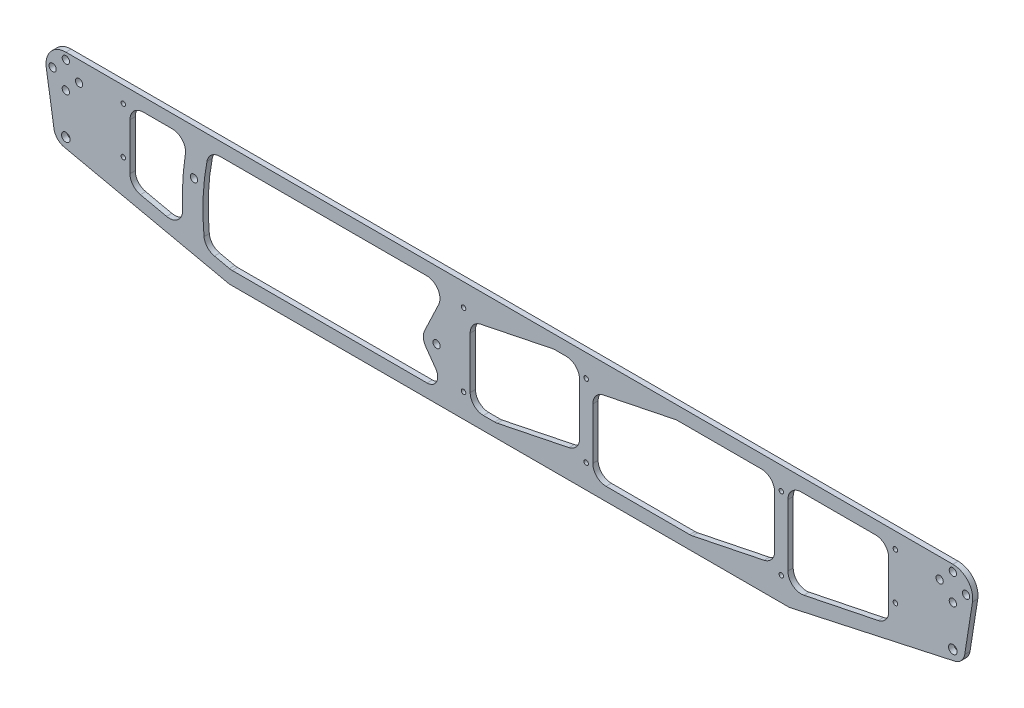
SolidWorks part; units mm, degrees
material "Сплав 2024"
ref_plane "Спереди" through (0, 0, 0) normal (0, 0, 1) x (1, 0, 0)
ref_plane "Сверху" through (0, 0, 0) normal (0, 1, 0) x (1, 0, 0)
ref_plane "Справа" through (0, 0, 0) normal (1, 0, 0) x (0, 0, -1)
sketch "Эскиз1" plane through (0, 0, 0) normal (0, 0, 1) x (1, 0, 0)
  line L0 (-349.8183, 27.6724) -> (-342.9109, -16.3036)
  line L1 (-350, 45) -> (350, 45) construction
  line L2 (-350, 45) -> (-350, -45) construction
  line L3 (-350, -45) -> (350, -45) construction
  line L4 (350, 45) -> (350, -45) construction
  line L5 (-350, 45) -> (350, -45) construction
  line L6 (-350, -45) -> (350, 45) construction
  line L7 (-342.9109, -16.3036) -> (-211.4811, -45)
  line L9 (0, 62.4154) -> (0, -74.3401) construction
  line L10 (-211.4811, -45) -> (211.4811, -45)
  line L12 (-335, 45) -> (335, 45)
  line L15 (342.9109, -16.3036) -> (211.4811, -45)
  line L16 (349.8183, 27.6724) -> (342.9109, -16.3036)
  arc A0 (-335, 45) -> (-349.8183, 27.6724) centre (-335, 30) ccw
  arc A1 (335, 45) -> (349.8183, 27.6724) centre (335, 30) cw
  circle A2 centre (-335, -10.6353) radius 3.25
  circle A3 centre (335, -10.6353) radius 3.25
  point P0 (0, 0)
  point P20 (0, 45)
  point P21 (0, -45)
  dimension "D3" = 30
  dimension "D4" = 6.5
  dimension "D1" = 700
  dimension "D2" = 90
extrude "Бобышка-Вытянуть1" add sketch "Эскиз1" along normal blind 4
sketch "Эскиз2" plane through (0, 0, 4) normal (0, 0, 1) x (1, 0, 0)
  line L0 (0, 49.4785) -> (0, -75.5602) construction
  line L1 (-350, 30) -> (-320, 30) construction
  line L2 (-335, 45) -> (-335, 15) construction
  line L3 (335, 45) -> (335, 15) construction
  line L4 (350, 30) -> (320, 30) construction
  circle A0 centre (-335, 30) radius 15 construction
  arc A1 (-335, 45) -> (-349.8183, 27.6724) centre (-335, 30) ccw construction
  circle A2 centre (-335, 30) radius 10 construction
  circle A4 centre (335, 30) radius 10 construction
  circle A5 centre (335, 30) radius 15 construction
  dimension "D2" = 20
hole_wizard "Отверстие с зазором M51" positions "Эскиз4" profile "Эскиз3" hole size "M5" standard "Ansi Metric" end condition through all
sketch "Эскиз4" plane through (0, 0, 4) normal (0, 0, 1) x (1, 0, 0)
  line L0 (-335, 45) -> (-335, 15) construction
  line L1 (-350, 30) -> (-320, 30) construction
  line L2 (350, 30) -> (320, 30) construction
  line L3 (335, 45) -> (335, 15) construction
  circle A0 centre (-335, 30) radius 10 construction
  circle A1 centre (335, 30) radius 10 construction
  point P0 (-335, 40)
  point P6 (-345, 30)
  point P10 (-335, 20)
  point P12 (-325, 30)
  point P34 (325, 30)
  point P40 (335, 40)
  point P44 (345, 30)
  point P46 (335, 20)
sketch "Эскиз3" plane through (-335, 40, 4) normal (1, 0, 0) x (0, -1, 0)
  line L0 (0, 0) -> (0, 4)
  line L1 (0, 4) -> (2.75, 4)
  line L2 (2.75, 4) -> (2.75, 0)
  line L5 (2.75, 0) -> (0, 0)
  line L11 (0, -6.35) -> (0, 107.95) construction
  dimension "Диаметр сквозного отверстия" = 5.5
  dimension "Глубина сквозного отверстия" = 4
sketch "Эскиз7" plane through (0, 0, 0) normal (0, 0, -1) x (-1, 0, 0)
  line L0 (211.4811, -45) -> (-211.4811, -45) construction
  arc A0 (349.8183, 27.6724) -> (335, 45) centre (335, 30) ccw construction
  point P0 (55, -6)
  point P4 (238.23, 10.84)
  dimension "D1" = 183.23
  dimension "D2" = 16.84
  dimension "D3" = 280
  dimension "D4" = 39
hole_wizard "Отверстие с зазором M52" positions "Эскиз9" profile "Эскиз8" hole size "M5" standard "Ansi Metric" end condition through all
sketch "Эскиз9" plane through (0, 0, 0) normal (0, 0, -1) x (-1, 0, 0)
  point P0 (55, -6)
  point P3 (238.23, 10.84)
sketch "Эскиз8" plane through (-55, -6, 0) normal (1, 0, 0) x (0, 1, 0)
  line L0 (0, 0) -> (0, 4)
  line L1 (0, 4) -> (2.75, 4)
  line L2 (2.75, 4) -> (2.75, 0)
  line L5 (2.75, 0) -> (0, 0)
  line L11 (0, -6.35) -> (0, 107.95) construction
  dimension "Диаметр сквозного отверстия" = 5.5
  dimension "Глубина сквозного отверстия" = 4
sketch "Эскиз10" plane through (0, 0, 4) normal (0, 0, 1) x (1, 0, 0)
  line L0 (-286.5713, 35) -> (-242.5713, 35)
  line L1 (335, 45) -> (-335, 45) construction
  line L2 (-286.5713, 35) -> (-286.5713, -18.3692)
  line L3 (-286.5713, -18.3692) -> (-245.8185, -27.2672)
  line L4 (0, 45) -> (0, -45) construction
  line L5 (-342.9109, -16.3036) -> (-211.4811, -45) construction
  line L6 (-226.6719, 35) -> (-46.5878, 35)
  line L7 (-210.4021, -35) -> (-46.5878, -35)
  line L8 (-211.4811, -45) -> (211.4811, -45) construction
  line L9 (-210.4021, -35) -> (-229.7525, -30.775)
  line L10 (-46.5878, 35) -> (-64.032, -1.7078)
  line L11 (-46.5878, -35) -> (-63.1395, -11.8093)
  line L12 (286.5713, 35) -> (286.5713, -18.3692)
  line L13 (286.5713, -18.3692) -> (210.4021, -34)
  line L14 (286.5713, 35) -> (210.4021, 35)
  line L15 (210.4021, 35) -> (210.4021, -34)
  line L16 (210.4021, -42) -> (210.4021, 43) construction
  line L17 (200.4021, 35) -> (126.1451, 35)
  line L18 (200.4021, -42) -> (200.4021, 43) construction
  line L19 (-29.5979, -42) -> (-29.5979, 43) construction
  line L20 (-29.5979, 22.0494) -> (-29.5979, -35)
  line L21 (-29.5979, -35) -> (-10.0721, -35)
  line L22 (200.4021, -22.0494) -> (200.4021, 35)
  line L23 (53.0365, 35) -> (53.0365, -22.0494)
  line L24 (63.0365, 22.0494) -> (63.0365, -35)
  line L25 (33.5107, 35) -> (-29.5979, 22.0494)
  line L26 (200.4021, -22.0494) -> (137.2934, -35)
  line L28 (63.0365, -35) -> (137.2934, -35)
  line L29 (126.1451, 35) -> (63.0365, 22.0494)
  line L30 (53.0365, -22.0494) -> (-10.0721, -35)
  line L34 (53.0365, 35) -> (33.5107, 35)
  arc A0 (-64.032, -1.7078) -> (-63.1395, -11.8093) centre (-55, -6) ccw
  arc A2 (-242.5713, 35) -> (-245.8185, -27.2672) centre (-55, -6) ccw
  arc A3 (-226.6719, 35) -> (-229.7525, -30.775) centre (-55, -6) ccw
  dimension "D4" = 384
  dimension "D5" = 353
  dimension "D2" = 20
  dimension "D1" = 10
  dimension "D3" = 10
  dimension "D6" = 10
  dimension "D7" = 10
  dimension "D8" = 10
  dimension "D9" = 44
  dimension "D10" = 10
  dimension "D11" = 57.0494
extrude "Вырез-Вытянуть3" cut sketch "Эскиз10" against normal through all
fillet "Скругление2" radius 10 16 edges at (-46.5878, 35, 2) (-210.4021, -35, 2) (-229.7525, -30.775, 2) (-226.6719, 35, 2) (-242.5713, 35, 2) (-245.8185, -27.2672, 2) (-286.5713, -18.3692, 2) (-286.5713, 35, 2) (-342.9109, -16.3036, 2) (-211.4811, -45, 2) (211.4811, -45, 2) (342.9109, -16.3036, 2) (286.5713, 35, 2) (286.5713, -18.3692, 2) (210.4021, 35, 2) (210.4021, -34, 2)
fillet "Скругление3" radius 10 12 edges at (-29.5979, -35, 2) (200.4021, 35, 2) (53.0365, 35, 2) (200.4021, -22.0494, 2) (137.2934, -35, 2) (33.5107, 35, 2) (-29.5979, 22.0494, 2) (63.0365, -35, 2) (126.1451, 35, 2) (63.0365, 22.0494, 2) (53.0365, -22.0494, 2) (-10.0721, -35, 2)
sketch "Эскиз11" plane through (0, 0, 4) normal (0, 0, 1) x (1, 0, 0)
  line L0 (205.4021, 45) -> (205.4021, -45) construction
  line L1 (335, 45) -> (-335, 45) construction
  line L2 (-210.4021, -45) -> (210.4021, -45) construction
  line L3 (200.4021, -13.8931) -> (200.4021, 25) construction
  line L4 (199.8709, -27) -> (211.9144, -27) construction
  line L5 (202.3145, 28) -> (208.249, 28) construction
  line L6 (-34.5979, 45) -> (-34.5979, -45) construction
  line L7 (-29.5979, 13.8931) -> (-29.5979, -25) construction
  line L8 (-39.6608, -27) -> (-30.9685, -27) construction
  line L9 (-37.6326, 28) -> (-30.9685, 28) construction
  line L10 (291.5713, 36.1496) -> (291.5713, -11.5594) construction
  line L11 (286.5713, -10.2129) -> (286.5713, 25) construction
  line L12 (294.823, -2) -> (288.4097, -2) construction
  line L13 (294.823, 33) -> (288.4097, 33) construction
  line L14 (0, 45) -> (0, 71.0849) construction
  line L15 (-294.823, 33) -> (-288.4097, 33) construction
  line L16 (-294.823, -2) -> (-288.4097, -2) construction
  line L17 (-291.5713, 36.1496) -> (-291.5713, -11.5594) construction
  line L18 (58.0365, 45) -> (58.0365, -45) construction
  line L19 (53.0365, -13.8931) -> (53.0365, 25) construction
  line L20 (53.8048, -27) -> (63.1419, -27) construction
  line L21 (64.656, 28) -> (53.8048, 28) construction
  dimension "D1" = 5
  dimension "D2" = 18
  dimension "D3" = 55
  dimension "D4" = 5
  dimension "D5" = 18
  dimension "D6" = 55
  dimension "D7" = 5
  dimension "D8" = 35
  dimension "D9" = 5
  dimension "D10" = 18
  dimension "D11" = 55
hole_wizard "Отверстие с зазором M31" positions "Эскиз13" profile "Эскиз12" hole size "M3" standard "Ansi Metric" end condition through all
sketch "Эскиз13" plane through (0, 0, 4) normal (0, 0, 1) x (1, 0, 0)
  line L0 (-34.5979, 45) -> (-34.5979, -45) construction
  line L1 (-37.6326, 28) -> (-30.9685, 28) construction
  line L2 (-39.6608, -27) -> (-30.9685, -27) construction
  line L3 (205.4021, 45) -> (205.4021, -45) construction
  line L4 (199.8709, -27) -> (211.9144, -27) construction
  line L5 (202.3145, 28) -> (208.249, 28) construction
  line L6 (291.5713, 36.1496) -> (291.5713, -11.5594) construction
  line L7 (294.823, 33) -> (288.4097, 33) construction
  line L8 (294.823, -2) -> (288.4097, -2) construction
  line L9 (-294.823, -2) -> (-288.4097, -2) construction
  line L10 (-294.823, 33) -> (-288.4097, 33) construction
  line L11 (-291.5713, 36.1496) -> (-291.5713, -11.5594) construction
  line L12 (58.0365, 45) -> (58.0365, -45) construction
  line L13 (64.656, 28) -> (53.8048, 28) construction
  line L14 (53.8048, -27) -> (63.1419, -27) construction
  point P0 (-34.5979, 28)
  point P6 (-34.5979, -27)
  point P10 (205.4021, -27)
  point P16 (205.4021, 28)
  point P22 (291.5713, 33)
  point P28 (291.6163, -2)
  point P32 (-291.6163, -2)
  point P36 (-291.5713, 33)
  point P49 (58.0365, 28)
  point P55 (58.0365, -27)
sketch "Эскиз12" plane through (-34.5979, 28, 4) normal (1, 0, 0) x (0, -1, 0)
  line L0 (0, 0) -> (0, 4)
  line L1 (0, 4) -> (1.7, 4)
  line L2 (1.7, 4) -> (1.7, 0)
  line L5 (1.7, 0) -> (0, 0)
  line L11 (0, -6.35) -> (0, 107.95) construction
  dimension "Диаметр сквозного отверстия" = 3.4
  dimension "Глубина сквозного отверстия" = 4
sketch "Эскиз14" plane through (0, 0, 4) normal (0, 0, 1) x (1, 0, 0)
  line L0 (0, 59.2479) -> (0, -65.4566) construction
fillet "Скругление4" radius 8 1 edges at (-46.5878, -35, 2)
